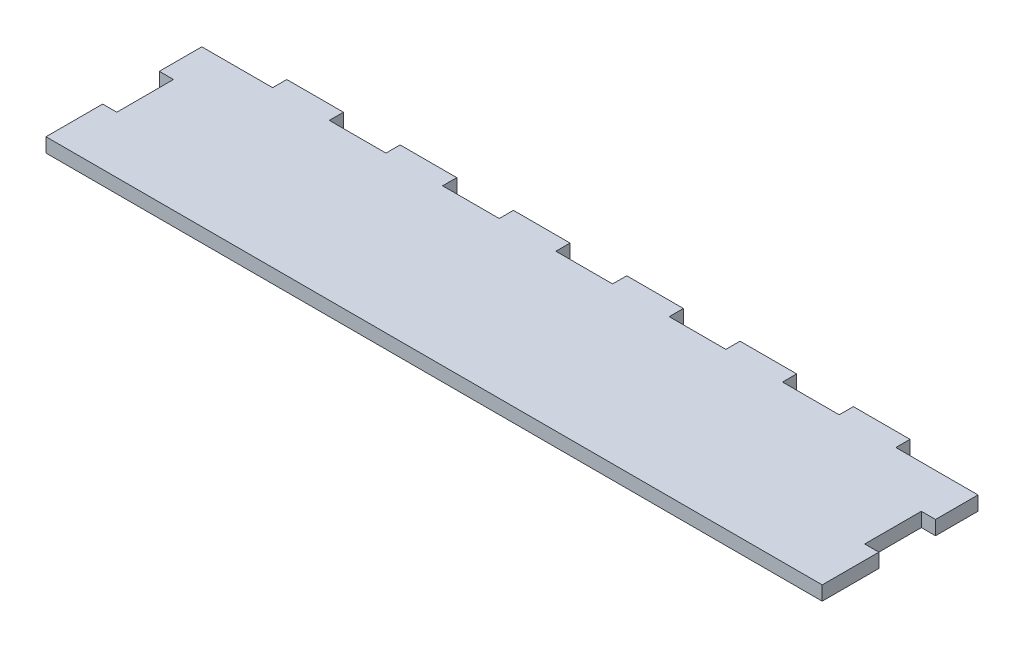
SolidWorks part; units mm, degrees
ref_plane "Front Plane" through (0, 0, 0) normal (0, 0, 1) x (1, 0, 0)
ref_plane "Top Plane" through (0, 0, 0) normal (0, 1, 0) x (1, 0, 0)
ref_plane "Right Plane" through (0, 0, 0) normal (1, 0, 0) x (0, 0, -1)
sketch "Sketch1" plane through (0, 0, 0) normal (0, 1, 0) x (1, 0, 0)
  line L1 (-86.995, -19.05) -> (86.995, -19.05)
  line L2 (-86.995, -19.05) -> (-86.995, 19.05)
  line L3 (-86.995, 19.05) -> (86.995, 19.05)
  line L4 (86.995, -19.05) -> (86.995, 19.05)
  line L5 (-86.995, -19.05) -> (86.995, 19.05) construction
  line L6 (-86.995, 19.05) -> (86.995, -19.05) construction
  point P0 (0, 0)
  dimension "D1" = 38.1
  dimension "D2" = 173.99
extrude "Boss-Extrude1" add sketch "Sketch1" along normal blind 3.175
sketch "Sketch2" plane through (0, 3.175, 0) normal (0, 1, 0) x (1, 0, 0)
  line L0 (86.995, 19.05) -> (-86.995, 19.05) construction
  line L1 (-86.995, 19.05) -> (-71.12, 19.05)
  line L2 (-86.995, 19.05) -> (-86.995, 15.875)
  line L3 (-86.995, 15.875) -> (-71.12, 15.875)
  line L4 (-71.12, 19.05) -> (-71.12, 15.875)
  line L5 (-58.42, 19.05) -> (-45.72, 19.05)
  line L6 (-58.42, 19.05) -> (-58.42, 15.875)
  line L7 (-58.42, 15.875) -> (-45.72, 15.875)
  line L8 (-45.72, 19.05) -> (-45.72, 15.875)
  line L9 (-33.02, 19.05) -> (-33.02, 15.875)
  line L10 (-33.02, 19.05) -> (-20.32, 19.05)
  line L11 (-20.32, 19.05) -> (-20.32, 15.875)
  line L12 (-33.02, 15.875) -> (-20.32, 15.875)
  line L13 (-7.62, 19.05) -> (-7.62, 15.875)
  line L14 (-7.62, 19.05) -> (5.08, 19.05)
  line L15 (5.08, 19.05) -> (5.08, 15.875)
  line L16 (-7.62, 15.875) -> (5.08, 15.875)
  line L17 (17.78, 19.05) -> (17.78, 15.875)
  line L18 (17.78, 19.05) -> (30.48, 19.05)
  line L19 (30.48, 19.05) -> (30.48, 15.875)
  line L20 (17.78, 15.875) -> (30.48, 15.875)
  line L21 (43.18, 19.05) -> (43.18, 15.875)
  line L22 (43.18, 19.05) -> (55.88, 19.05)
  line L23 (55.88, 19.05) -> (55.88, 15.875)
  line L24 (43.18, 15.875) -> (55.88, 15.875)
  line L25 (68.58, 19.05) -> (68.58, 15.875)
  line L26 (68.58, 19.05) -> (81.28, 19.05)
  line L28 (68.58, 15.875) -> (81.28, 15.875)
  line L29 (81.28, 19.05) -> (81.28, 15.875) [skipped]
  line L30 (81.28, 19.05) -> (86.995, 19.05)
  line L31 (86.995, 19.05) -> (86.995, 15.875)
  line L32 (86.995, -19.05) -> (86.995, 19.05) construction
  line L33 (86.995, 15.875) -> (81.28, 15.875)
  line L34 (-86.995, 19.05) -> (-86.995, -19.05) construction
  line L35 (-86.995, 6.35) -> (-83.82, 6.35)
  line L36 (-86.995, 6.35) -> (-86.995, -6.35)
  line L37 (-86.995, -6.35) -> (-83.82, -6.35)
  line L38 (-83.82, 6.35) -> (-83.82, -6.35)
  line L39 (-86.995, -19.05) -> (86.995, -19.05) construction
  line L40 (0, 0) -> (0, -30.1115) construction
  line L41 (86.995, -6.35) -> (83.82, -6.35)
  line L42 (83.82, 6.35) -> (83.82, -6.35)
  line L43 (86.995, 6.35) -> (83.82, 6.35)
  line L44 (86.995, 6.35) -> (86.995, -6.35)
  dimension "D1" = 15.875
  dimension "D2" = 12.7
  dimension "D3" = 12.7
  dimension "D4" = 3.175
  dimension "D5" = 3.175
  dimension "D7" = 12.7
  dimension "D8" = 12.7
  dimension "D9" = 3.175
  dimension "D6" = 6
extrude "Cut-Extrude1" cut sketch "Sketch2" against normal blind 3.175
